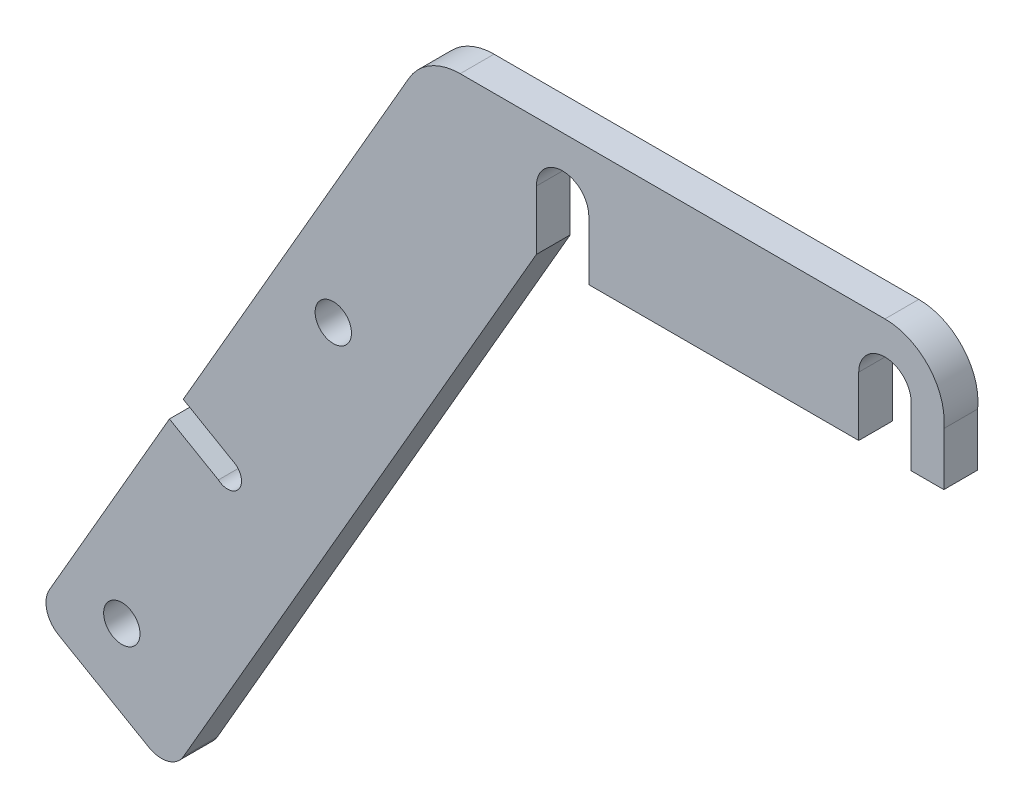
SolidWorks part; units mm, degrees
ref_plane "Front Plane" through (0, 0, 0) normal (0, 0, 1) x (1, 0, 0)
ref_plane "Top Plane" through (0, 0, 0) normal (0, 1, 0) x (1, 0, 0)
ref_plane "Right Plane" through (0, 0, 0) normal (1, 0, 0) x (0, 0, -1)
sketch "Sketch1" plane through (0, 0, 0) normal (0, 0, 1) x (1, 0, 0)
  line L0 (-3.1, -7) -> (-3.1, 0)
  line L1 (3.1, 0) -> (3.1, -7)
  line L2 (3.1, -7) -> (35.005, -7)
  line L3 (35.005, -7) -> (35.005, 0)
  line L4 (41.205, 0) -> (41.205, -7)
  line L5 (41.205, -7) -> (45.0649, -7)
  line L6 (45.0649, -7) -> (45.0649, -0.748)
  line L7 (-12.1067, 0) -> (-52.1067, -69.282) construction
  line L8 (-18.1688, 3.5) -> (-44.8438, -42.7025)
  line L9 (-3.1, -7) -> (-44.8206, -79.2622)
  line L10 (-12.1067, 7) -> (38.105, 7)
  line L11 (-12.1067, 0) -> (61.5392, 0) construction
  line L12 (3.1, -7) -> (-3.1, -7) construction
  line L13 (-58.1688, -65.782) -> (-42.3206, -74.932) construction
  line L14 (-38.7817, -46.2025) -> (-44.8438, -42.7025)
  line L15 (-40.6904, -48.8756) -> (-46.4785, -45.5338)
  line L16 (-46.4785, -45.5338) -> (-60.6688, -70.1122)
  line L17 (-59.5708, -74.2102) -> (-48.9187, -80.3602)
  arc A0 (3.1, 0) -> (-3.1, 0) centre (0, 0) ccw
  arc A1 (41.205, 0) -> (35.005, 0) centre (38.105, 0) ccw
  arc A2 (45.0649, -0.748) -> (38.105, 7) centre (38.105, 0) ccw
  arc A3 (-18.1688, 3.5) -> (-12.1067, 7) centre (-12.1067, 0) cw
  circle A4 centre (-52.1067, -69.282) radius 2.15
  circle A5 centre (-27.1067, -25.9808) radius 2.15
  arc A6 (-59.5708, -74.2102) -> (-60.6688, -70.1122) centre (-58.0708, -71.6122) cw
  arc A7 (-40.6904, -48.8756) -> (-38.7817, -46.2025) centre (-39.6067, -47.6314) ccw
  arc A8 (-48.9187, -80.3602) -> (-44.8206, -79.2622) centre (-47.4187, -77.7622) ccw
  dimension "D1" = 3.1
  dimension "D2" = 7
  dimension "D5" = 3.3
  dimension "D8" = 4.3
  dimension "D10" = 25
  dimension "D11" = 3
  dimension "D12" = 3
  dimension "D3" = 120
  dimension "D4" = 7
  dimension "D6" = 80
  dimension "D7" = 50
  dimension "D9" = 38.105
  dimension "D13" = 8
extrude "Boss-Extrude1" add sketch "Sketch1" along normal blind 4
